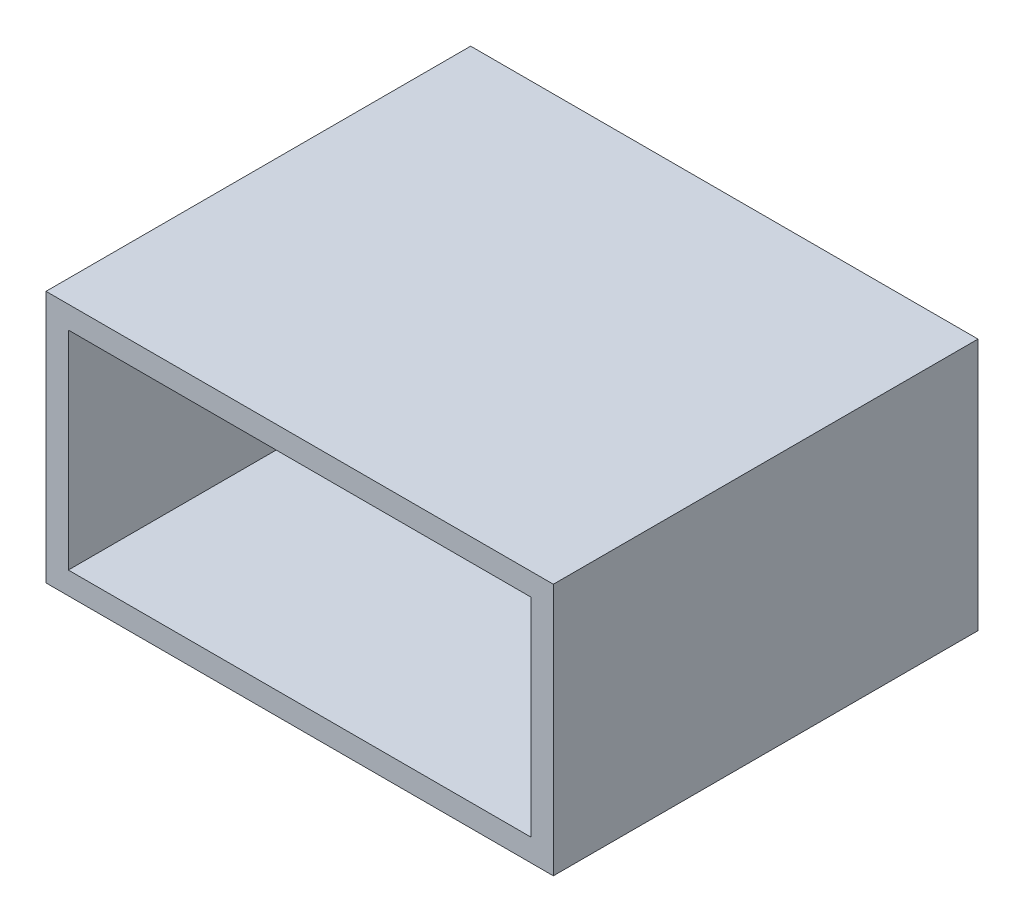
SolidWorks part; units mm, degrees
ref_plane "前视基准面" through (0, 0, 0) normal (0, 0, 1) x (1, 0, 0)
ref_plane "上视基准面" through (0, 0, 0) normal (0, 1, 0) x (1, 0, 0)
ref_plane "右视基准面" through (0, 0, 0) normal (1, 0, 0) x (0, 0, -1)
sketch "草图1" plane through (0, 0, 0) normal (0, 0, 1) x (1, 0, 0)
  line L1 (-5.175, -2.325) -> (5.175, -2.325)
  line L2 (-5.175, -2.325) -> (-5.175, 2.325)
  line L3 (-5.175, 2.325) -> (5.175, 2.325)
  line L4 (5.175, -2.325) -> (5.175, 2.325)
  line L5 (-5.175, -2.325) -> (5.175, 2.325) construction
  line L6 (-5.175, 2.325) -> (5.175, -2.325) construction
  point P0 (0, 0)
  dimension "D1" = 10.35
  dimension "D2" = 4.65
extrude "拉伸-薄壁1" add sketch "草图1" along normal blind 9.5 thin
scale "缩放比例1" scale about centroid uniform scaling yes scale factor 1.2
